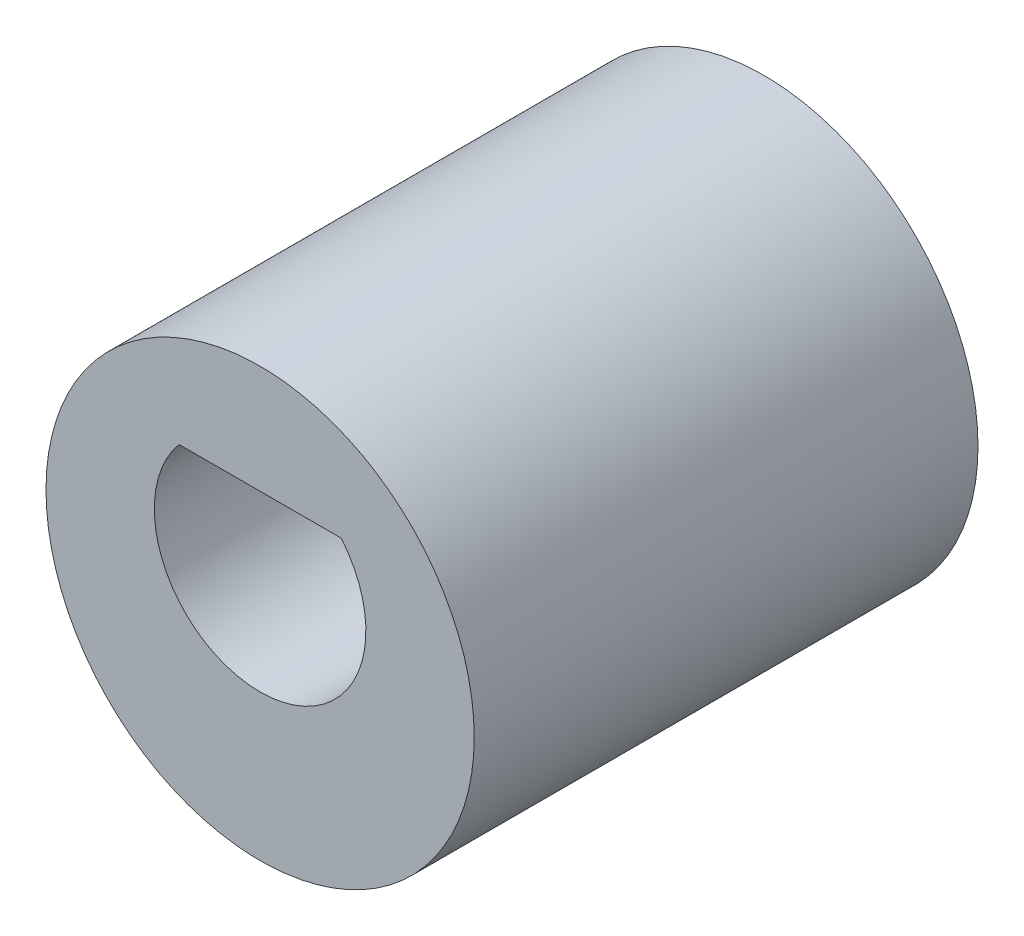
SolidWorks part; units mm, degrees
material "Custom Plastic"
ref_plane "Front Plane" through (0, 0, 0) normal (0, 0, 1) x (1, 0, 0)
ref_plane "Top Plane" through (0, 0, 0) normal (0, 1, 0) x (1, 0, 0)
ref_plane "Right Plane" through (0, 0, 0) normal (1, 0, 0) x (0, 0, -1)
sketch "Sketch2" plane through (0, 0, 0) normal (0, 0, 1) x (1, 0, 0)
  circle A0 centre (0, 0) radius 8.5
  circle A1 centre (0, 1.5) radius 0.5
  dimension "D1" = 17
  dimension "D2" = 1
  dimension "D3" = 1.5
extrude "Boss-Extrude1" add sketch "Sketch2" along normal blind 20
sketch "Sketch3" plane through (0, 0, 0) normal (0, 0, 1) x (1, 0, 0)
  line L0 (0, 1.5) -> (5, 1.5) construction
  line L1 (0, 1.5) -> (-5, 1.5) construction
  circle A0 centre (0, 1.5) radius 0.5 construction
  circle A1 centre (0, 1.5) radius 0.5
  circle A2 centre (-5, 1.5) radius 2.3
  circle A3 centre (5, 1.5) radius 2.3
  dimension "D1" = 4.6
  dimension "D2" = 4.6
  dimension "D3" = 5
extrude "Cut-Extrude1" cut sketch "Sketch3" along normal blind 6
sketch "Sketch4" plane through (0, 0, 20) normal (0, 0, 1) x (1, 0, 0)
  circle A0 centre (0, 0) radius 8.5 construction
  circle A1 centre (0, 0) radius 8.5
  circle A2 centre (0, 0) radius 10.5
  dimension "D1" = 2
sketch "Sketch5" plane through (0, 0, 20) normal (0, 0, 1) x (1, 0, 0)
  line L0 (-3.1225, 4) -> (3.1225, 4) construction
  line L1 (-3.2171, 4.2) -> (3.2171, 4.2)
  circle A0 centre (0, 1.5) radius 4 construction
  arc A1 (-3.2171, 4.2) -> (3.2171, 4.2) centre (0, 1.5) ccw
  circle A2 centre (0, 1.5) radius 4.2 construction
  dimension "D1" = 8
  dimension "D2" = 2.5
  dimension "D4" = 0.2
  dimension "D3" = 0.2
extrude "Cut-Extrude2" cut sketch "Sketch5" against normal blind 12
